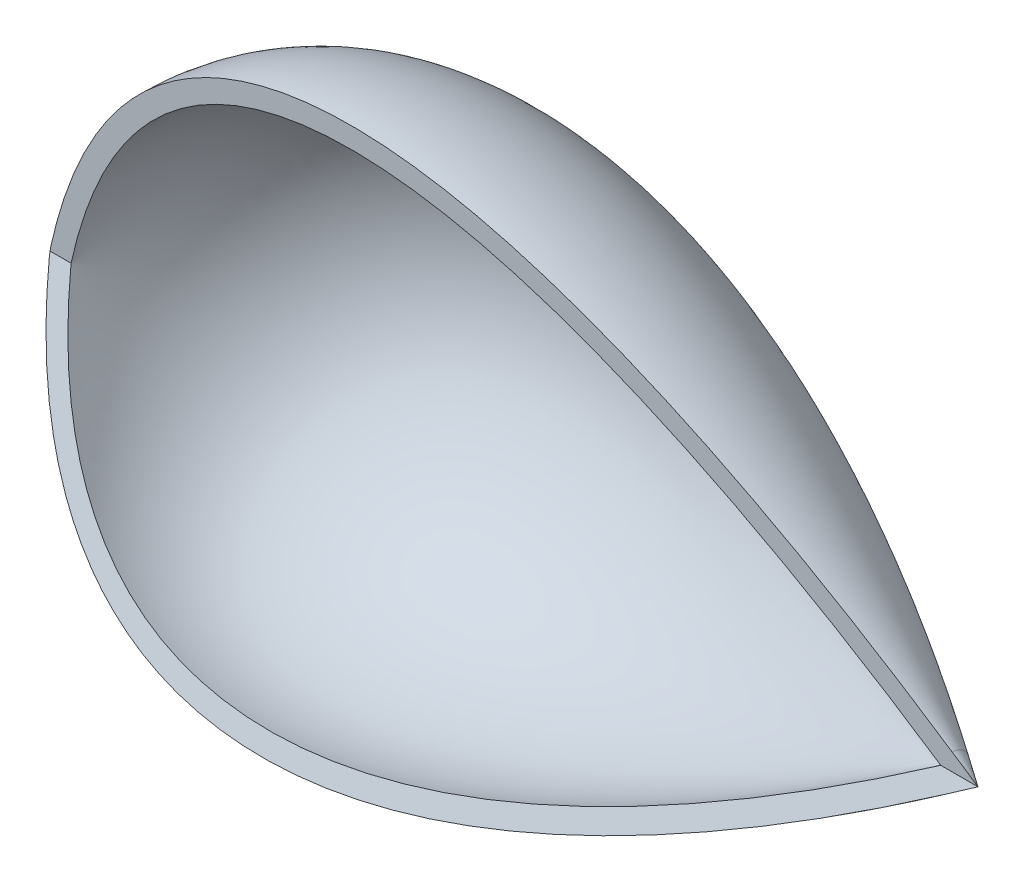
SolidWorks part; units mm, degrees
ref_plane "Front Plane" through (0, 0, 0) normal (0, 0, 1) x (1, 0, 0)
ref_plane "Top Plane" through (0, 0, 0) normal (0, 1, 0) x (1, 0, 0)
ref_plane "Right Plane" through (0, 0, 0) normal (1, 0, 0) x (0, 0, -1)
sketch "Sketch2" plane through (0, 0, 0) normal (0, 0, 1) x (1, 0, 0)
  line L0 (79.375, 0) -> (49.2125, 0) construction
  line L1 (0, 7.9375) -> (0, 22.5735) construction
  line L2 (104.1935, 116.8935) -> (-71.5348, -58.8348) construction
  line L3 (-3.2127, 0) -> (0, 0)
  line L4 (135.1146, 2.6395) -> (139.0627, 0)
  line L5 (139.0627, 0) -> (133.35, 0)
  arc A0 (-3.1004, 0.6844) -> (-3.2127, 0) centre (3.1004, -0.6844) ccw
  spline S0 degree 3 poles (0, 0) (12.2666, 55.5654) (71.2858, 41.4922) (133.35, 0) knots 0 0 0 0 1 1 1 1
  spline S1 degree 1 poles (-3.1004, 0.6844) (135.1146, 2.6395) knots 0 0 1 1 construction
  spline S2 degree 3 poles (-3.1004, 0.6844) (-2.9039, 1.5743) (-2.4769, 3.3656) (-1.5363, 6.7731) (-0.1766, 10.8086) (1.7391, 15.2662) (4.6694, 20.7115) (9.0255, 26.5823) (15.2921, 32.1174) (22.4708, 36.1362) (33.063, 39.535) (47.8994, 40.3459) (64.4017, 37.2428) (78.4129, 32.7219) (89.2724, 28.378) (100.4296, 23.1457) (111.8249, 17.0895) (121.4786, 11.4024) (129.2479, 6.5116) (133.174, 3.9368) (135.1146, 2.6395) knots 0 0 0 0 0.015625 0.03125 0.0625 0.09375 0.125 0.1875 0.25 0.3125 0.375 0.5 0.625 0.6875 0.75 0.8125 0.875 0.9375 0.96875 1 1 1 1
  dimension "D5" = 3.175
  dimension "D1" = 133.35
  dimension "D2" = 12.7
  dimension "D3" = 25.4
  dimension "D4" = 45
revolve "Revolve1" add sketch "Sketch2" angle 200 about L0
